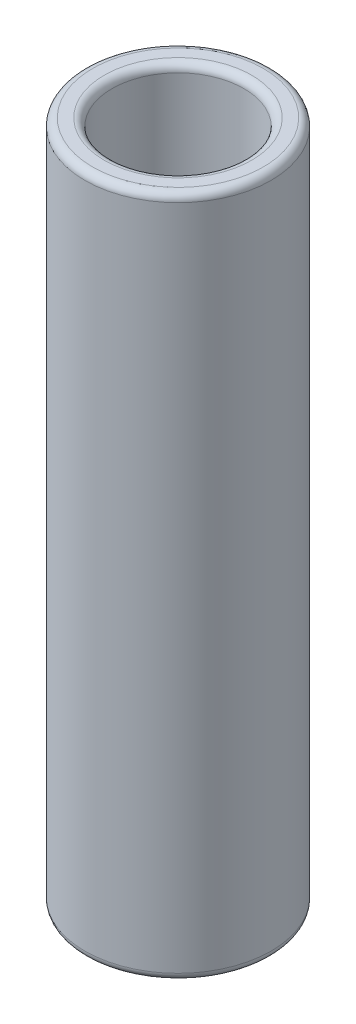
SolidWorks part; units mm, degrees
ref_plane "Alzado" through (0, 0, 0) normal (0, 0, 1) x (1, 0, 0)
ref_plane "Planta" through (0, 0, 0) normal (0, 1, 0) x (1, 0, 0)
ref_plane "Vista lateral" through (0, 0, 0) normal (1, 0, 0) x (0, 0, -1)
sketch "Croquis1" plane through (0, 0, 0) normal (0, 1, 0) x (1, 0, 0)
  circle A0 centre (0, 0) radius 6
  circle A1 centre (0, 0) radius 4.25
  dimension "D1" = 12
  dimension "D2" = 8.5
extrude "Saliente-Extruir1" add sketch "Croquis1" along normal blind 44
fillet "Redondeo1" radius 0.5 4 edges at (0, 0, 6) (0, 44, 6) (0, 0, 4.25) (0, 44, 4.25)
